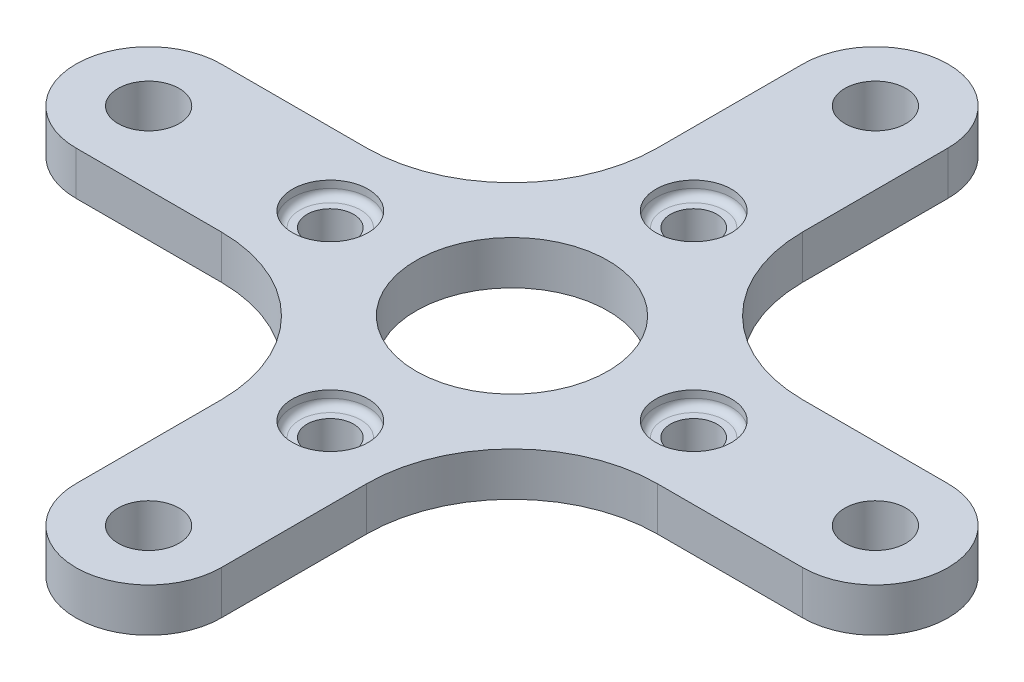
SolidWorks part; units mm, degrees
ref_plane "Front Plane" through (0, 0, 0) normal (0, 0, 1) x (1, 0, 0)
ref_plane "Top Plane" through (0, 0, 0) normal (0, 1, 0) x (1, 0, 0)
ref_plane "Right Plane" through (0, 0, 0) normal (1, 0, 0) x (0, 0, -1)
sketch "Sketch1" plane through (0, 0, 0) normal (0, 1, 0) x (1, 0, 0)
  line L0 (-30, 0) -> (30, 0) construction
  line L1 (0, -30) -> (0, 30) construction
  line L2 (-5, 25) -> (-5, 15)
  line L3 (0, 0) -> (-27.2346, 27.2346) construction
  line L4 (5, 25) -> (5, 15)
  line L5 (25, 5) -> (15, 5)
  line L6 (25, -5) -> (15, -5)
  line L7 (5, -25) -> (5, -15)
  line L8 (-5, -25) -> (-5, -15)
  line L9 (-25, -5) -> (-15, -5)
  line L10 (-25, 5) -> (-15, 5)
  circle A0 centre (0, 0) radius 6.6
  circle A1 centre (0, 0) radius 12.5 construction
  circle A2 centre (0, 0) radius 25 construction
  circle A3 centre (0, 12.5) radius 1.6
  circle A4 centre (12.5, 0) radius 1.6
  circle A5 centre (0, -12.5) radius 1.6
  circle A6 centre (-12.5, 0) radius 1.6
  circle A7 centre (0, 25) radius 2.1
  circle A8 centre (25, 0) radius 2.1
  circle A9 centre (0, -25) radius 2.1
  circle A10 centre (-25, 0) radius 2.1
  arc A11 (-5, 25) -> (5, 25) centre (0, 25) cw
  arc A12 (-5, 15) -> (-15, 5) centre (-15, 15) cw
  arc A13 (5, 15) -> (15, 5) centre (15, 15) ccw
  arc A14 (25, 5) -> (25, -5) centre (25, 0) cw
  arc A15 (15, 5) -> (5, 15) centre (15, 15) cw
  arc A16 (15, -5) -> (5, -15) centre (15, -15) ccw
  arc A17 (5, -25) -> (-5, -25) centre (0, -25) cw
  arc A18 (5, -15) -> (15, -5) centre (15, -15) cw
  arc A19 (-5, -15) -> (-15, -5) centre (-15, -15) ccw
  arc A20 (-25, -5) -> (-25, 5) centre (-25, 0) cw
  arc A21 (-15, -5) -> (-5, -15) centre (-15, -15) cw
  arc A22 (-15, 5) -> (-5, 15) centre (-15, 15) ccw
  point P8 (0, 0)
  point P11 (0, 0)
  point P22 (0, 0)
  point P31 (0, 0)
  point P33 (0, 30)
  point P70 (0, 0)
  dimension "D1" = 13.2
  dimension "D2" = 25
  dimension "D3" = 50
  dimension "D4" = 3.2
  dimension "D6" = 4.2
  dimension "D9" = 5
  dimension "D8" = 60
  dimension "D10" = 10
  dimension "D11" = 10
  dimension "D12" = 45
  dimension "D5" = 4
  dimension "D7" = 4
  dimension "D13" = 4
extrude "Boss-Extrude1" add sketch "Sketch1" along normal blind 3 contours A20 L9 A19 L8 A17 L7 A16 L6 A14 L5 A13 L4 A11 L2 A12 L10 A10 A9 A8 A7 A6 A5 A4 A3 A0
sketch "Sketch2" plane through (0, 3, 0) normal (0, 1, 0) x (1, 0, 0)
  circle A0 centre (0, 12.5) radius 2.6
  circle A1 centre (12.5, 0) radius 2.6
  circle A2 centre (0, -12.5) radius 2.6
  circle A3 centre (-12.5, 0) radius 2.6
  circle A4 centre (0, -12.5) radius 1.6 construction
  circle A5 centre (12.5, 0) radius 1.6 construction
  circle A6 centre (0, 12.5) radius 1.6 construction
  circle A7 centre (-12.5, 0) radius 1.6 construction
  circle A8 centre (0, -12.5) radius 1.6
  circle A9 centre (12.5, 0) radius 1.6
  circle A10 centre (0, 12.5) radius 1.6
  circle A11 centre (-12.5, 0) radius 1.6
  point P12 (0, 0)
  dimension "D1" = 5.2
  dimension "D2" = 4
extrude "Cut-Extrude1" cut sketch "Sketch2" against normal blind 1
fillet "Fillet1" radius 0.5 4 edges at (0, 2, 15.1) (12.5, 2, 2.6) (0, 2, -9.9) (-12.5, 2, 2.6)
